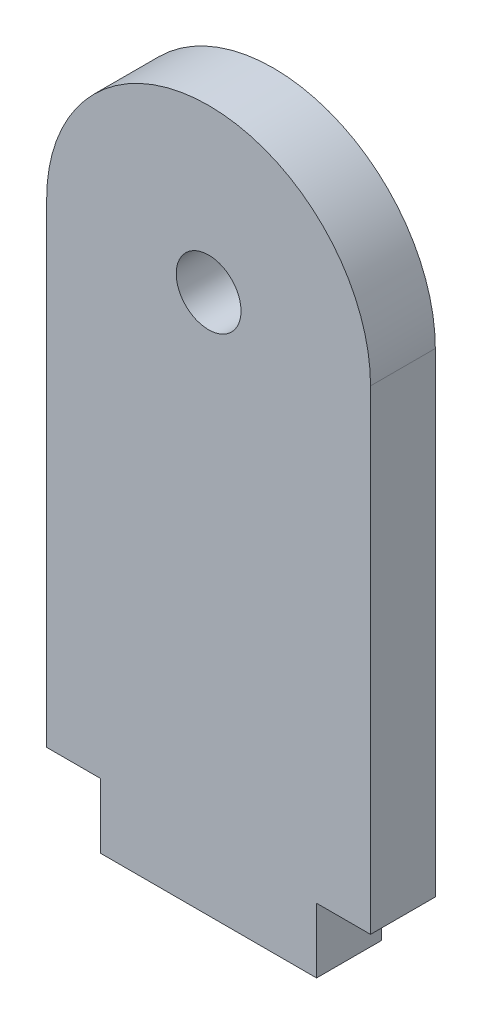
SolidWorks part; units mm, degrees
ref_plane "前视基准面" through (0, 0, 0) normal (0, 0, 1) x (1, 0, 0)
ref_plane "上视基准面" through (0, 0, 0) normal (0, 1, 0) x (1, 0, 0)
ref_plane "右视基准面" through (0, 0, 0) normal (1, 0, 0) x (0, 0, -1)
sketch "草图1" plane through (0, 0, 0) normal (0, 0, 1) x (1, 0, 0)
  line L0 (7.5, 0) -> (7.5, -22)
  line L1 (0, 0) -> (15, 0)
  line L2 (0, 0) -> (0, -22)
  line L3 (0, -22) -> (15, -22)
  line L4 (15, 0) -> (15, -22)
  line L5 (2.5, -22) -> (12.5, -22)
  line L6 (2.5, -22) -> (2.5, -25)
  line L7 (2.5, -25) -> (12.5, -25)
  line L8 (12.5, -22) -> (12.5, -25)
  circle A0 centre (7.5, 0) radius 7.5
  circle A1 centre (7.5, 0) radius 1.5
  dimension "D6" = 3
  dimension "D1" = 22
  dimension "D2" = 15
  dimension "D3" = 3
  dimension "D4" = 10
  dimension "D5" = 5
extrude "凸台-拉伸1" add sketch "草图1" along normal blind 3 contours A1 L1 A0 | A1 L1 A0 L0 | A1 L0 A0 L1 | A0 L0 L3 L4 | A0 L2 L3 L0 | L8 L3 L6 L7
